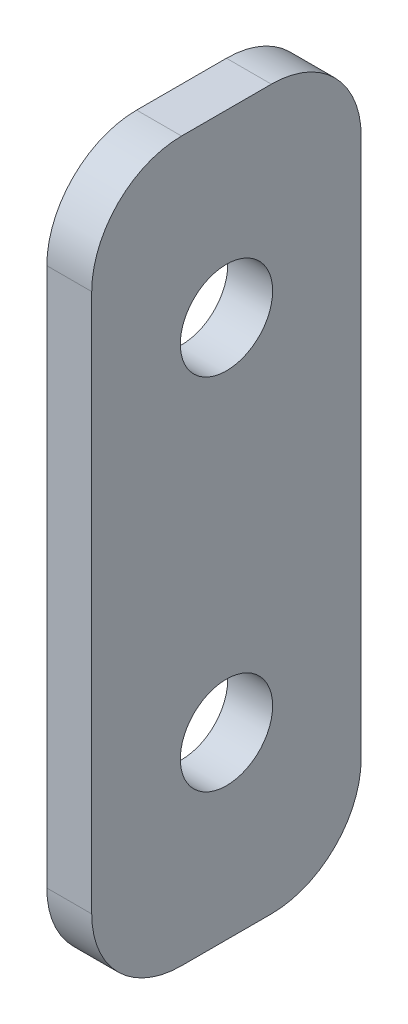
SolidWorks part; units mm, degrees
ref_plane "Front Plane" through (0, 0, 0) normal (0, 0, 1) x (1, 0, 0)
ref_plane "Top Plane" through (0, 0, 0) normal (0, 1, 0) x (1, 0, 0)
ref_plane "Right Plane" through (0, 0, 0) normal (1, 0, 0) x (0, 0, -1)
sketch "Sketch1" plane through (0, 0, 0) normal (1, 0, 0) x (0, 0, -1)
  line L1 (-9.525, 25.4) -> (9.525, 25.4)
  line L2 (-9.525, 25.4) -> (-9.525, -25.4)
  line L3 (-9.525, -25.4) -> (9.525, -25.4)
  line L4 (9.525, 25.4) -> (9.525, -25.4)
  line L5 (-9.525, 25.4) -> (9.525, -25.4) construction
  line L6 (-9.525, -25.4) -> (9.525, 25.4) construction
  point P0 (0, 0)
  dimension "D1" = 50.8
  dimension "D2" = 19.05
extrude "Boss-Extrude1" add sketch "Sketch1" along normal mid plane 3.175
sketch "Sketch4" plane through (1.5875, 0, 0) normal (1, 0, 0) x (0, 0, -1)
  line L0 (0, 12.7) -> (0, -12.7) construction
  point P0 (0, 12.7)
  point P2 (0, -12.7)
  dimension "D1" = 25.4
hole_wizard "1/4 Clearance Hole1" positions "Sketch4" profile "Sketch3" hole size "1/4" standard "ANSI Inch" end condition through all
sketch "Sketch3" plane through (1.5875, 12.7, 0) normal (0, 1, 0) x (0, 0, -1)
  line L0 (0, 0) -> (0, 3.175)
  line L1 (0, 3.175) -> (3.2639, 3.175)
  line L2 (3.2639, 3.175) -> (3.2639, 0)
  line L5 (3.2639, 0) -> (0, 0)
  line L11 (0, -6.35) -> (0, 107.95) construction
  dimension "Thru Hole Dia." = 6.5278
  dimension "Thru Hole Depth" = 3.175
fillet "Fillet1" radius 6.35 4 edges at (0, -25.4, 9.525) (0, -25.4, -9.525) (0, 25.4, -9.525) (0, 25.4, 9.525)
